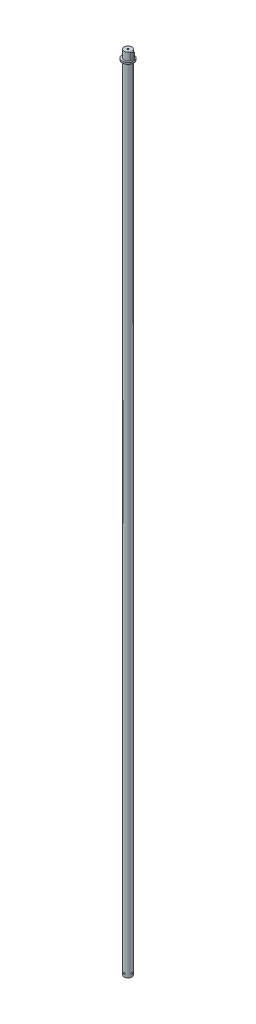
SolidWorks part; units mm, degrees
ref_plane "Front Plane" through (0, 0, 0) normal (0, 0, 1) x (1, 0, 0)
ref_plane "Top Plane" through (0, 0, 0) normal (0, 1, 0) x (1, 0, 0)
ref_plane "Right Plane" through (0, 0, 0) normal (1, 0, 0) x (0, 0, -1)
sketch "Sketch1" plane through (0, 0, 0) normal (0, 1, 0) x (1, 0, 0)
  circle A0 centre (0, 0) radius 5
  dimension "D1" = 10
extrude "Boss-Extrude1" add sketch "Sketch1" along normal blind 1050
ref_plane "Plane1" through (0, 1040, 0) normal (0, 1, 0) x (1, 0, 0)
sketch "Sketch2" plane through (0, 1040, 0) normal (0, 1, 0) x (1, 0, 0)
  circle A0 centre (0, 0) radius 7.5
  dimension "D1" = 15
extrude "Boss-Extrude2" add sketch "Sketch2" against normal blind 2
sketch "Sketch4" plane through (0, 1040, 0) normal (0, 1, 0) x (1, 0, 0)
  line L0 (0, 0) -> (7.5, 0) construction
  line L1 (4.899, 1) -> (7.433, 1)
  line L2 (4.899, -1) -> (7.433, -1)
  circle A1 centre (0, 0) radius 7.5
  circle A2 centre (0, 0) radius 7.5
  circle A3 centre (0, 0) radius 5
  circle A4 centre (0, 0) radius 5
  circle M6 centre (0, 0) radius 5
  circle M7 centre (0, 0) radius 7.5
  dimension "D3" = 1
  dimension "D1" = 0
  dimension "D2" = 0
extrude "Boss-Extrude4" add sketch "Sketch4" along normal up to surface (10 mm away) contours L0 A2 L1 M6 | L0 A4 L2 M7 up to face at (0, 1050, 5)
sketch "Sketch8" plane through (0, 1050, 0) normal (0, 1, 0) x (1, 0, 0)
  circle A0 centre (0, 0) radius 1
  dimension "D1" = 2
extrude "Cut-Extrude1" cut sketch "Sketch8" against normal blind 3
sketch "Sketch9" plane through (0, 0, 0) normal (0, 0, 1) x (1, 0, 0)
  line L0 (-5, 0) -> (5, 0) construction
  line L1 (-5, 0) -> (5, 0) construction
  circle A0 centre (0, 4) radius 1
  dimension "D1" = 2
  dimension "D2" = 4
extrude "Cut-Extrude2" cut sketch "Sketch9" against normal blind 10
pattern_circular "CirPattern1" count 4 over 360 about axis through (0, 1050, 0) along (0, -1, 0) of "Cut-Extrude2"
